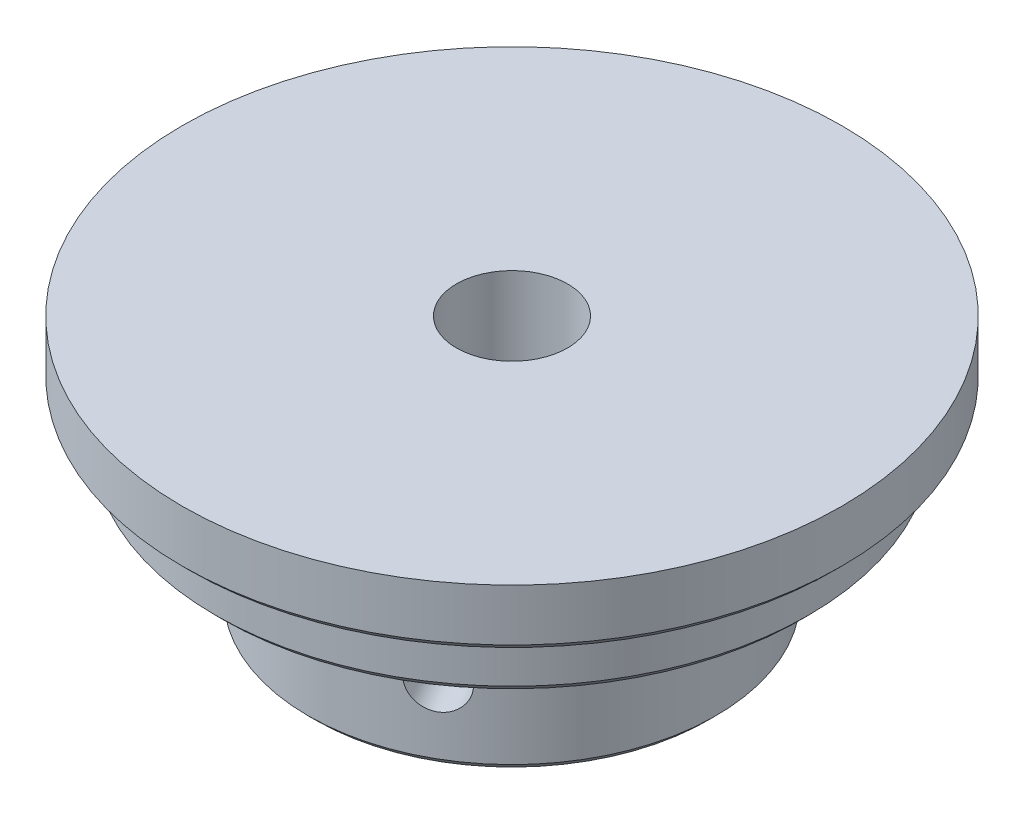
SolidWorks part; units mm, degrees
ref_plane "Piano frontale" through (0, 0, 0) normal (0, 0, 1) x (1, 0, 0)
ref_plane "Piano superiore" through (0, 0, 0) normal (0, 1, 0) x (1, 0, 0)
ref_plane "Piano destro" through (0, 0, 0) normal (1, 0, 0) x (0, 0, -1)
sketch "Schizzo2" plane through (0, 0, 0) normal (0, 0, 1) x (1, 0, 0)
  line L8 (0, 0) -> (0, -38.6738) construction
  line L9 (0, 0) -> (0, -34)
  line L10 (0, -34) -> (27.5, -34)
  line L11 (27.5, -34) -> (27.5, -16)
  line L12 (27.5, -16) -> (40, -16)
  line L13 (40, -16) -> (40, -8)
  line L14 (40, -8) -> (44.5, -8)
  line L15 (44.5, -8) -> (44.5, 0)
  line L16 (44.5, 0) -> (0, 0)
  line L17 (27.5, -25) -> (0, -25) construction
  dimension "D1" = 34
  dimension "D2" = 16
  dimension "D3" = 8
  dimension "D4" = 89
  dimension "D5" = 80
  dimension "D6" = 55
revolve "Rivoluzione2" add sketch "Schizzo2" angle 360 about L8
hole_wizard "Foro Ø15.0 (15)-1" positions "Schizzo3D3" profile "Schizzo5" hole size "Ø15.0" standard "ISO" end condition up to next
sketch3d "Schizzo3D3"
  point P1 (0, 0, 0)
sketch "Schizzo5" plane through (0, 0, 0) normal (1, 0, 0) x (0, 0, 1)
  line L0 (0, 0) -> (0, 34)
  line L1 (0, 34) -> (7.5, 34)
  line L2 (7.5, 34) -> (7.5, 0)
  line L5 (7.5, 0) -> (0, 0)
  line L11 (0, -6.35) -> (0, 107.95) construction
  dimension "Thru Hole Dia." = 15
  dimension "Thru Hole Depth" = 34
ref_plane "Piano1" through (-27.5, 0, 0) normal (-1, 0, 0) x (0, 0, 1)
hole_wizard "Foro Ø11.0 (11)-2" positions "Schizzo3D10" profile "Schizzo11" hole size "Ø11.0" standard "ISO" end condition up to next
sketch3d "Schizzo3D10"
  line L0 (0, 0, 0) -> (-27.3677, 0, 0)
  line L1 (-27.3677, 0, 0) -> (-27.5, -34, -0.0336)
  line L5 (-27.5, -34, -0.0336) -> (-27.4611, -24.0001, -0.0237) construction
  circle A0 centre (0, -34, 0) radius 27.5 construction
  point P7 (0, -6.5, 0)
  point P17 (-27.4611, -24.0001, -0.0237)
  point P20 (-27.4611, -24.0001, -0.0237)
  point P22 (-27.4611, -24.0001, -0.0237)
  point P24 (-27.4611, -24.0001, -0.0237)
  point P25 (-27.4611, -24.0001, -0.0237)
  point P27 (-27.4611, -24.0001, -0.0237)
  point P31 (-27.4611, -24.0001, -0.0237)
  point P33 (-27.4611, -24.0001, -0.0237)
  point P37 (-27.4611, -24.0001, -0.0237)
  point P42 (-27.4611, -24.0001, -0.0237)
  point P44 (-27.4611, -24.0001, -0.0237)
  point P46 (-27.4611, -24.0001, -0.0237)
  point P50 (-27.4611, -24.0001, -0.0237)
  point P52 (-27.5, -24.0001, -0.0238)
  dimension "D1" = 10
sketch "Schizzo11" plane through (-27.5, -24.0001, -0.0238) normal (0, 1, 0) x (-0.0009, 0, 1)
  line L0 (0, 0) -> (0, 27.5)
  line L1 (0, 27.5) -> (5.5, 27.5)
  line L2 (5.5, 27.5) -> (5.5, 0)
  line L5 (5.5, 0) -> (0, 0)
  line L11 (0, -6.35) -> (0, 107.95) construction
  dimension "Thru Hole Dia." = 11
  dimension "Thru Hole Depth" = 27.5
ref_plane "Piano3" through (13.75, 0, 23.8157) normal (0.5, 0, 0.866) x (0, 1, 0)
sketch "Schizzo19" plane through (13.75, 0, 23.8157) normal (0.5, 0, 0.866) x (0, 1, 0)
  line L0 (0, 0) -> (-24, 0) construction
  line L1 (-34, 27.5) -> (-34, -27.5) construction
  dimension "D1" = 10
hole_wizard "Foro Ø7.0 (7)-1" positions "Schizzo3D15" profile "Schizzo20" hole size "Ø7.0" standard "ISO" end condition up to next
sketch3d "Schizzo3D15"
  point P0 (13.75, -24, 23.8157)
  point P3 (13.75, -24, 23.8157)
  point P5 (13.75, -24, 23.8157)
  point P7 (13.75, -24, 23.8157)
sketch "Schizzo20" plane through (13.75, -24, 23.8157) normal (0, 1, 0) x (0.866, 0, -0.5)
  line L0 (0, 0) -> (0, 27.5)
  line L1 (0, 27.5) -> (3.5, 27.5)
  line L2 (3.5, 27.5) -> (3.5, 0)
  line L5 (3.5, 0) -> (0, 0)
  line L11 (0, -6.35) -> (0, 107.95) construction
  dimension "Thru Hole Dia." = 7
  dimension "Thru Hole Depth" = 27.5
mirror "Specchia1" about plane through (0, 0, 0) normal (0, 0, 1) of "Foro Ø7.0 (7)-1"
chamfer "Smusso1" distance 1 angle 45 3 edges at (0, -8, 44.5) (0, -16, 40) (0, -34, 27.5)
